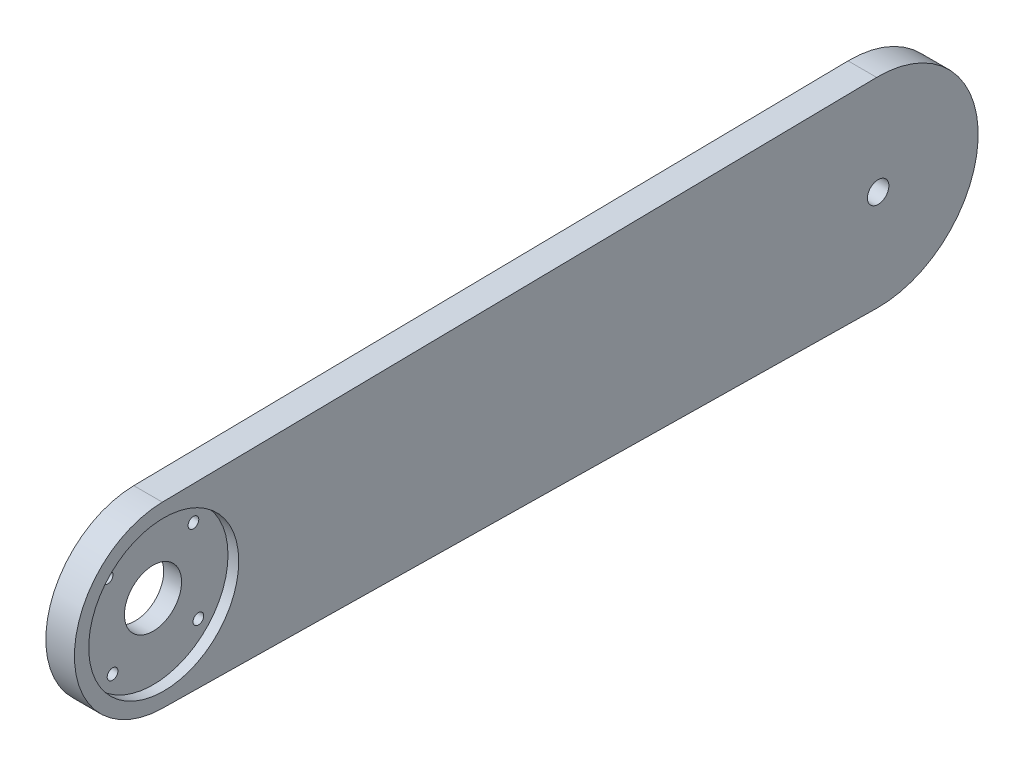
SolidWorks part; units mm, degrees
ref_plane "Alzado" through (0, 0, 0) normal (0, 0, 1) x (1, 0, 0)
ref_plane "Planta" through (0, 0, 0) normal (0, 1, 0) x (1, 0, 0)
ref_plane "Vista lateral" through (0, 0, 0) normal (1, 0, 0) x (0, 0, -1)
sketch "Croquis1" plane through (0, 0, 0) normal (1, 0, 0) x (0, 0, -1)
  line L0 (30, 0) -> (-98.2419, 0) construction
  line L1 (-70.1875, 12.4986) -> (29.79, 13.9984)
  line L2 (-70.1875, -12.4986) -> (29.79, -13.9984)
  circle A0 centre (30, 0) radius 1.5
  arc A1 (29.79, -13.9984) -> (29.79, 13.9984) centre (30, 0) ccw
  circle A2 centre (-70, 0) radius 4
  arc A3 (-70.1875, 12.4986) -> (-70.1875, -12.4986) centre (-70, 0) ccw
  dimension "D1" = 3
  dimension "D2" = 28
  dimension "D3" = 25
  dimension "D4" = 100
  dimension "D5" = 8
extrude "Saliente-Extruir1" add sketch "Croquis1" along normal blind 4
sketch "Croquis2" plane through (4, 0, 0) normal (1, 0, 0) x (0, 0, -1)
  circle A0 centre (-70, 0) radius 10.5
  dimension "D1" = 21
extrude "Cortar-Extruir1" cut sketch "Croquis2" against normal blind 1.5
sketch "Croquis3" plane through (0, 0, 0) normal (-1, 0, 0) x (0, 0, 1)
  line L0 (64.3419, 6.3481) -> (75.6581, -6.3481) construction
  line L1 (75.6581, -6.3481) -> (70, 0) construction
  line L2 (70, 0) -> (63.6519, -5.6581) construction
  line L3 (63.6519, -5.6581) -> (76.3481, 5.6581) construction
  circle A0 centre (63.6519, -5.6581) radius 0.75
  circle A1 centre (76.3481, 5.6581) radius 0.75
  circle A2 centre (64.3419, 6.3481) radius 0.75
  circle A3 centre (75.6581, -6.3481) radius 0.75
  dimension "D1" = 1.5
extrude "Cortar-Extruir2" cut sketch "Croquis3" against normal blind 10
